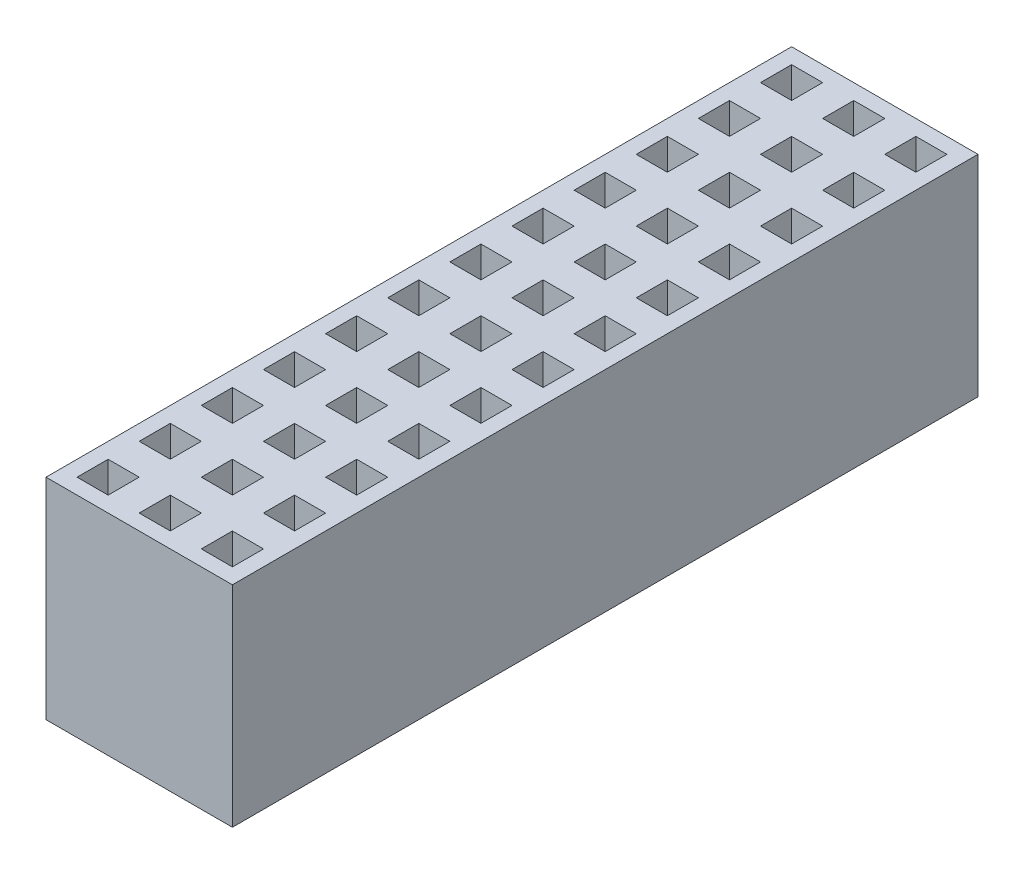
SolidWorks part; units mm, degrees
material "ABS"
ref_plane "Front Plane" through (0, 0, 0) normal (0, 0, 1) x (1, 0, 0)
ref_plane "Top Plane" through (0, 0, 0) normal (0, 1, 0) x (1, 0, 0)
ref_plane "Right Plane" through (0, 0, 0) normal (1, 0, 0) x (0, 0, -1)
sketch "Sketch1" plane through (0, 0, 0) normal (0, 1, 0) x (1, 0, 0)
  line L0 (-3.175, 13.335) -> (-1.905, 14.605) construction
  line L1 (-3.81, 15.24) -> (3.81, 15.24)
  line L2 (-3.81, 15.24) -> (-3.81, -15.24)
  line L3 (-3.81, -15.24) -> (3.81, -15.24)
  line L4 (3.81, 15.24) -> (3.81, -15.24)
  line L5 (-3.175, 14.605) -> (-1.905, 14.605)
  line L6 (-3.175, 14.605) -> (-3.175, 13.335)
  line L7 (-3.175, 13.335) -> (-1.905, 13.335)
  line L8 (-1.905, 14.605) -> (-1.905, 13.335)
  line L9 (-3.175, 14.605) -> (-1.905, 13.335) construction
  line L10 (-1.905, 13.335) -> (-1.8955, 13.298) construction
  line L11 (-0.635, 14.605) -> (0.635, 14.605)
  line L12 (-0.635, 14.605) -> (-0.635, 13.335)
  line L13 (-0.635, 13.335) -> (0.635, 13.335)
  line L14 (0.635, 14.605) -> (0.635, 13.335)
  line L15 (-0.635, 13.335) -> (0.635, 14.605) construction
  line L16 (-0.635, 14.605) -> (0.635, 13.335) construction
  line L17 (0.635, 13.335) -> (0.6445, 13.298) construction
  line L18 (1.905, 14.605) -> (3.175, 14.605)
  line L19 (1.905, 14.605) -> (1.905, 13.335)
  line L20 (1.905, 13.335) -> (3.175, 13.335)
  line L21 (3.175, 14.605) -> (3.175, 13.335)
  line L22 (1.905, 13.335) -> (3.175, 14.605) construction
  line L23 (1.905, 14.605) -> (3.175, 13.335) construction
  line L24 (3.175, 13.335) -> (3.1845, 13.298) construction
  line L25 (-3.175, 12.065) -> (-1.905, 12.065)
  line L26 (-3.175, 12.065) -> (-3.175, 10.795)
  line L27 (-3.175, 10.795) -> (-1.905, 10.795)
  line L28 (-1.905, 12.065) -> (-1.905, 10.795)
  line L29 (-3.175, 10.795) -> (-1.905, 12.065) construction
  line L30 (-3.175, 12.065) -> (-1.905, 10.795) construction
  line L31 (-1.905, 10.795) -> (-1.8955, 10.758) construction
  line L32 (-0.635, 12.065) -> (0.635, 12.065)
  line L33 (-0.635, 12.065) -> (-0.635, 10.795)
  line L34 (-0.635, 10.795) -> (0.635, 10.795)
  line L35 (0.635, 12.065) -> (0.635, 10.795)
  line L36 (-0.635, 10.795) -> (0.635, 12.065) construction
  line L37 (-0.635, 12.065) -> (0.635, 10.795) construction
  line L38 (0.635, 10.795) -> (0.6445, 10.758) construction
  line L39 (1.905, 12.065) -> (3.175, 12.065)
  line L40 (1.905, 12.065) -> (1.905, 10.795)
  line L41 (1.905, 10.795) -> (3.175, 10.795)
  line L42 (3.175, 12.065) -> (3.175, 10.795)
  line L43 (1.905, 10.795) -> (3.175, 12.065) construction
  line L44 (1.905, 12.065) -> (3.175, 10.795) construction
  line L45 (3.175, 10.795) -> (3.1845, 10.758) construction
  line L46 (-3.175, 9.525) -> (-1.905, 9.525)
  line L47 (-3.175, 9.525) -> (-3.175, 8.255)
  line L48 (-3.175, 8.255) -> (-1.905, 8.255)
  line L49 (-1.905, 9.525) -> (-1.905, 8.255)
  line L50 (-3.175, 8.255) -> (-1.905, 9.525) construction
  line L51 (-3.175, 9.525) -> (-1.905, 8.255) construction
  line L52 (-1.905, 8.255) -> (-1.8955, 8.218) construction
  line L53 (-0.635, 9.525) -> (0.635, 9.525)
  line L54 (-0.635, 9.525) -> (-0.635, 8.255)
  line L55 (-0.635, 8.255) -> (0.635, 8.255)
  line L56 (0.635, 9.525) -> (0.635, 8.255)
  line L57 (-0.635, 8.255) -> (0.635, 9.525) construction
  line L58 (-0.635, 9.525) -> (0.635, 8.255) construction
  line L59 (0.635, 8.255) -> (0.6445, 8.218) construction
  line L60 (1.905, 9.525) -> (3.175, 9.525)
  line L61 (1.905, 9.525) -> (1.905, 8.255)
  line L62 (1.905, 8.255) -> (3.175, 8.255)
  line L63 (3.175, 9.525) -> (3.175, 8.255)
  line L64 (1.905, 8.255) -> (3.175, 9.525) construction
  line L65 (1.905, 9.525) -> (3.175, 8.255) construction
  line L66 (3.175, 8.255) -> (3.1845, 8.218) construction
  line L67 (-3.175, 6.985) -> (-1.905, 6.985)
  line L68 (-3.175, 6.985) -> (-3.175, 5.715)
  line L69 (-3.175, 5.715) -> (-1.905, 5.715)
  line L70 (-1.905, 6.985) -> (-1.905, 5.715)
  line L71 (-3.175, 5.715) -> (-1.905, 6.985) construction
  line L72 (-3.175, 6.985) -> (-1.905, 5.715) construction
  line L73 (-1.905, 5.715) -> (-1.8955, 5.678) construction
  line L74 (-0.635, 6.985) -> (0.635, 6.985)
  line L75 (-0.635, 6.985) -> (-0.635, 5.715)
  line L76 (-0.635, 5.715) -> (0.635, 5.715)
  line L77 (0.635, 6.985) -> (0.635, 5.715)
  line L78 (-0.635, 5.715) -> (0.635, 6.985) construction
  line L79 (-0.635, 6.985) -> (0.635, 5.715) construction
  line L80 (0.635, 5.715) -> (0.6445, 5.678) construction
  line L81 (1.905, 6.985) -> (3.175, 6.985)
  line L82 (1.905, 6.985) -> (1.905, 5.715)
  line L83 (1.905, 5.715) -> (3.175, 5.715)
  line L84 (3.175, 6.985) -> (3.175, 5.715)
  line L85 (1.905, 5.715) -> (3.175, 6.985) construction
  line L86 (1.905, 6.985) -> (3.175, 5.715) construction
  line L87 (3.175, 5.715) -> (3.1845, 5.678) construction
  line L88 (-3.175, 4.445) -> (-1.905, 4.445)
  line L89 (-3.175, 4.445) -> (-3.175, 3.175)
  line L90 (-3.175, 3.175) -> (-1.905, 3.175)
  line L91 (-1.905, 4.445) -> (-1.905, 3.175)
  line L92 (-3.175, 3.175) -> (-1.905, 4.445) construction
  line L93 (-3.175, 4.445) -> (-1.905, 3.175) construction
  line L94 (-1.905, 3.175) -> (-1.8955, 3.138) construction
  line L95 (-0.635, 4.445) -> (0.635, 4.445)
  line L96 (-0.635, 4.445) -> (-0.635, 3.175)
  line L97 (-0.635, 3.175) -> (0.635, 3.175)
  line L98 (0.635, 4.445) -> (0.635, 3.175)
  line L99 (-0.635, 3.175) -> (0.635, 4.445) construction
  line L100 (-0.635, 4.445) -> (0.635, 3.175) construction
  line L101 (0.635, 3.175) -> (0.6445, 3.138) construction
  line L102 (1.905, 4.445) -> (3.175, 4.445)
  line L103 (1.905, 4.445) -> (1.905, 3.175)
  line L104 (1.905, 3.175) -> (3.175, 3.175)
  line L105 (3.175, 4.445) -> (3.175, 3.175)
  line L106 (1.905, 3.175) -> (3.175, 4.445) construction
  line L107 (1.905, 4.445) -> (3.175, 3.175) construction
  line L108 (3.175, 3.175) -> (3.1845, 3.138) construction
  line L109 (-3.175, 1.905) -> (-1.905, 1.905)
  line L110 (-3.175, 1.905) -> (-3.175, 0.635)
  line L111 (-3.175, 0.635) -> (-1.905, 0.635)
  line L112 (-1.905, 1.905) -> (-1.905, 0.635)
  line L113 (-3.175, 0.635) -> (-1.905, 1.905) construction
  line L114 (-3.175, 1.905) -> (-1.905, 0.635) construction
  line L115 (-1.905, 0.635) -> (-1.8955, 0.598) construction
  line L116 (-0.635, 1.905) -> (0.635, 1.905)
  line L117 (-0.635, 1.905) -> (-0.635, 0.635)
  line L118 (-0.635, 0.635) -> (0.635, 0.635)
  line L119 (0.635, 1.905) -> (0.635, 0.635)
  line L120 (-0.635, 0.635) -> (0.635, 1.905) construction
  line L121 (-0.635, 1.905) -> (0.635, 0.635) construction
  line L122 (0.635, 0.635) -> (0.6445, 0.598) construction
  line L123 (1.905, 1.905) -> (3.175, 1.905)
  line L124 (1.905, 1.905) -> (1.905, 0.635)
  line L125 (1.905, 0.635) -> (3.175, 0.635)
  line L126 (3.175, 1.905) -> (3.175, 0.635)
  line L127 (1.905, 0.635) -> (3.175, 1.905) construction
  line L128 (1.905, 1.905) -> (3.175, 0.635) construction
  line L129 (3.175, 0.635) -> (3.1845, 0.598) construction
  line L130 (-3.175, -0.635) -> (-1.905, -0.635)
  line L131 (-3.175, -0.635) -> (-3.175, -1.905)
  line L132 (-3.175, -1.905) -> (-1.905, -1.905)
  line L133 (-1.905, -0.635) -> (-1.905, -1.905)
  line L134 (-3.175, -1.905) -> (-1.905, -0.635) construction
  line L135 (-3.175, -0.635) -> (-1.905, -1.905) construction
  line L136 (-1.905, -1.905) -> (-1.8955, -1.942) construction
  line L137 (-0.635, -0.635) -> (0.635, -0.635)
  line L138 (-0.635, -0.635) -> (-0.635, -1.905)
  line L139 (-0.635, -1.905) -> (0.635, -1.905)
  line L140 (0.635, -0.635) -> (0.635, -1.905)
  line L141 (-0.635, -1.905) -> (0.635, -0.635) construction
  line L142 (-0.635, -0.635) -> (0.635, -1.905) construction
  line L143 (0.635, -1.905) -> (0.6445, -1.942) construction
  line L144 (1.905, -0.635) -> (3.175, -0.635)
  line L145 (1.905, -0.635) -> (1.905, -1.905)
  line L146 (1.905, -1.905) -> (3.175, -1.905)
  line L147 (3.175, -0.635) -> (3.175, -1.905)
  line L148 (1.905, -1.905) -> (3.175, -0.635) construction
  line L149 (1.905, -0.635) -> (3.175, -1.905) construction
  line L150 (3.175, -1.905) -> (3.1845, -1.942) construction
  line L151 (-3.175, -3.175) -> (-1.905, -3.175)
  line L152 (-3.175, -3.175) -> (-3.175, -4.445)
  line L153 (-3.175, -4.445) -> (-1.905, -4.445)
  line L154 (-1.905, -3.175) -> (-1.905, -4.445)
  line L155 (-3.175, -4.445) -> (-1.905, -3.175) construction
  line L156 (-3.175, -3.175) -> (-1.905, -4.445) construction
  line L157 (-1.905, -4.445) -> (-1.8955, -4.482) construction
  line L158 (-0.635, -3.175) -> (0.635, -3.175)
  line L159 (-0.635, -3.175) -> (-0.635, -4.445)
  line L160 (-0.635, -4.445) -> (0.635, -4.445)
  line L161 (0.635, -3.175) -> (0.635, -4.445)
  line L162 (-0.635, -4.445) -> (0.635, -3.175) construction
  line L163 (-0.635, -3.175) -> (0.635, -4.445) construction
  line L164 (0.635, -4.445) -> (0.6445, -4.482) construction
  line L165 (1.905, -3.175) -> (3.175, -3.175)
  line L166 (1.905, -3.175) -> (1.905, -4.445)
  line L167 (1.905, -4.445) -> (3.175, -4.445)
  line L168 (3.175, -3.175) -> (3.175, -4.445)
  line L169 (1.905, -4.445) -> (3.175, -3.175) construction
  line L170 (1.905, -3.175) -> (3.175, -4.445) construction
  line L171 (3.175, -4.445) -> (3.1845, -4.482) construction
  line L172 (-3.175, -5.715) -> (-1.905, -5.715)
  line L173 (-3.175, -5.715) -> (-3.175, -6.985)
  line L174 (-3.175, -6.985) -> (-1.905, -6.985)
  line L175 (-1.905, -5.715) -> (-1.905, -6.985)
  line L176 (-3.175, -6.985) -> (-1.905, -5.715) construction
  line L177 (-3.175, -5.715) -> (-1.905, -6.985) construction
  line L178 (-1.905, -6.985) -> (-1.8955, -7.022) construction
  line L179 (-0.635, -5.715) -> (0.635, -5.715)
  line L180 (-0.635, -5.715) -> (-0.635, -6.985)
  line L181 (-0.635, -6.985) -> (0.635, -6.985)
  line L182 (0.635, -5.715) -> (0.635, -6.985)
  line L183 (-0.635, -6.985) -> (0.635, -5.715) construction
  line L184 (-0.635, -5.715) -> (0.635, -6.985) construction
  line L185 (0.635, -6.985) -> (0.6445, -7.022) construction
  line L186 (1.905, -5.715) -> (3.175, -5.715)
  line L187 (1.905, -5.715) -> (1.905, -6.985)
  line L188 (1.905, -6.985) -> (3.175, -6.985)
  line L189 (3.175, -5.715) -> (3.175, -6.985)
  line L190 (1.905, -6.985) -> (3.175, -5.715) construction
  line L191 (1.905, -5.715) -> (3.175, -6.985) construction
  line L192 (3.175, -6.985) -> (3.1845, -7.022) construction
  line L193 (-3.175, -8.255) -> (-1.905, -8.255)
  line L194 (-3.175, -8.255) -> (-3.175, -9.525)
  line L195 (-3.175, -9.525) -> (-1.905, -9.525)
  line L196 (-1.905, -8.255) -> (-1.905, -9.525)
  line L197 (-3.175, -9.525) -> (-1.905, -8.255) construction
  line L198 (-3.175, -8.255) -> (-1.905, -9.525) construction
  line L199 (-1.905, -9.525) -> (-1.8955, -9.562) construction
  line L200 (-0.635, -8.255) -> (0.635, -8.255)
  line L201 (-0.635, -8.255) -> (-0.635, -9.525)
  line L202 (-0.635, -9.525) -> (0.635, -9.525)
  line L203 (0.635, -8.255) -> (0.635, -9.525)
  line L204 (-0.635, -9.525) -> (0.635, -8.255) construction
  line L205 (-0.635, -8.255) -> (0.635, -9.525) construction
  line L206 (0.635, -9.525) -> (0.6445, -9.562) construction
  line L207 (1.905, -8.255) -> (3.175, -8.255)
  line L208 (1.905, -8.255) -> (1.905, -9.525)
  line L209 (1.905, -9.525) -> (3.175, -9.525)
  line L210 (3.175, -8.255) -> (3.175, -9.525)
  line L211 (1.905, -9.525) -> (3.175, -8.255) construction
  line L212 (1.905, -8.255) -> (3.175, -9.525) construction
  line L213 (3.175, -9.525) -> (3.1845, -9.562) construction
  line L214 (-3.175, -10.795) -> (-1.905, -10.795)
  line L215 (-3.175, -10.795) -> (-3.175, -12.065)
  line L216 (-3.175, -12.065) -> (-1.905, -12.065)
  line L217 (-1.905, -10.795) -> (-1.905, -12.065)
  line L218 (-3.175, -12.065) -> (-1.905, -10.795) construction
  line L219 (-3.175, -10.795) -> (-1.905, -12.065) construction
  line L220 (-1.905, -12.065) -> (-1.8955, -12.102) construction
  line L221 (-0.635, -10.795) -> (0.635, -10.795)
  line L222 (-0.635, -10.795) -> (-0.635, -12.065)
  line L223 (-0.635, -12.065) -> (0.635, -12.065)
  line L224 (0.635, -10.795) -> (0.635, -12.065)
  line L225 (-0.635, -12.065) -> (0.635, -10.795) construction
  line L226 (-0.635, -10.795) -> (0.635, -12.065) construction
  line L227 (0.635, -12.065) -> (0.6445, -12.102) construction
  line L228 (1.905, -10.795) -> (3.175, -10.795)
  line L229 (1.905, -10.795) -> (1.905, -12.065)
  line L230 (1.905, -12.065) -> (3.175, -12.065)
  line L231 (3.175, -10.795) -> (3.175, -12.065)
  line L232 (1.905, -12.065) -> (3.175, -10.795) construction
  line L233 (1.905, -10.795) -> (3.175, -12.065) construction
  line L234 (3.175, -12.065) -> (3.1845, -12.102) construction
  line L235 (-3.175, -13.335) -> (-1.905, -13.335)
  line L236 (-3.175, -13.335) -> (-3.175, -14.605)
  line L237 (-3.175, -14.605) -> (-1.905, -14.605)
  line L238 (-1.905, -13.335) -> (-1.905, -14.605)
  line L239 (-3.175, -14.605) -> (-1.905, -13.335) construction
  line L240 (-3.175, -13.335) -> (-1.905, -14.605) construction
  line L241 (-1.905, -14.605) -> (-1.8955, -14.642) construction
  line L242 (-0.635, -13.335) -> (0.635, -13.335)
  line L243 (-0.635, -13.335) -> (-0.635, -14.605)
  line L244 (-0.635, -14.605) -> (0.635, -14.605)
  line L245 (0.635, -13.335) -> (0.635, -14.605)
  line L246 (-0.635, -14.605) -> (0.635, -13.335) construction
  line L247 (-0.635, -13.335) -> (0.635, -14.605) construction
  line L248 (0.635, -14.605) -> (0.6445, -14.642) construction
  line L249 (1.905, -13.335) -> (3.175, -13.335)
  line L250 (1.905, -13.335) -> (1.905, -14.605)
  line L251 (1.905, -14.605) -> (3.175, -14.605)
  line L252 (3.175, -13.335) -> (3.175, -14.605)
  line L253 (1.905, -14.605) -> (3.175, -13.335) construction
  line L254 (1.905, -13.335) -> (3.175, -14.605) construction
  line L255 (3.175, -14.605) -> (3.1845, -14.642) construction
  point P4 (0, -15.24)
  point P5 (3.81, 0)
  point P6 (0, 0)
  point P12 (-2.54, 13.97)
  point P21 (0, 13.97)
  point P27 (2.54, 13.97)
  point P33 (-2.54, 11.43)
  point P39 (0, 11.43)
  point P45 (2.54, 11.43)
  point P51 (-2.54, 8.89)
  point P57 (0, 8.89)
  point P63 (2.54, 8.89)
  point P69 (-2.54, 6.35)
  point P75 (0, 6.35)
  point P81 (2.54, 6.35)
  point P87 (-2.54, 3.81)
  point P93 (0, 3.81)
  point P99 (2.54, 3.81)
  point P105 (-2.54, 1.27)
  point P111 (0, 1.27)
  point P117 (2.54, 1.27)
  point P123 (-2.54, -1.27)
  point P129 (0, -1.27)
  point P135 (2.54, -1.27)
  point P141 (-2.54, -3.81)
  point P147 (0, -3.81)
  point P153 (2.54, -3.81)
  point P159 (-2.54, -6.35)
  point P165 (0, -6.35)
  point P171 (2.54, -6.35)
  point P177 (-2.54, -8.89)
  point P183 (0, -8.89)
  point P189 (2.54, -8.89)
  point P195 (-2.54, -11.43)
  point P201 (0, -11.43)
  point P207 (2.54, -11.43)
  point P213 (-2.54, -13.97)
  point P219 (0, -13.97)
  point P225 (2.54, -13.97)
  dimension "D1" = 7.62
  dimension "D2" = 30.48
  dimension "D3" = 1.27
  dimension "D4" = 1.27
  dimension "D5" = 1.27
  dimension "D6" = 1.27
  dimension "D7" = 3
  dimension "D8" = 12
extrude "Boss-Extrude1" add sketch "Sketch1" along normal blind 8.5852
